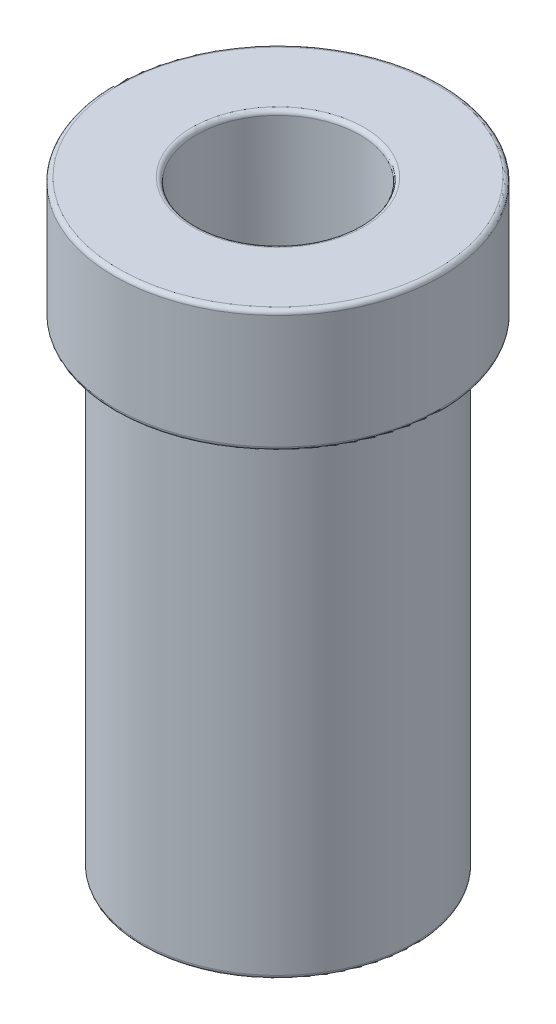
SolidWorks part; units mm, degrees
material "6061 Alloy"
ref_plane "Front Plane" through (0, 0, 0) normal (0, 0, 1) x (1, 0, 0)
ref_plane "Top Plane" through (0, 0, 0) normal (0, 1, 0) x (1, 0, 0)
ref_plane "Right Plane" through (0, 0, 0) normal (1, 0, 0) x (0, 0, -1)
sketch "Sketch1" plane through (0, 0, 0) normal (0, 0, 1) x (1, 0, 0)
  line L0 (0, 0) -> (0, -0.6875) construction
  line L1 (0, -0.6875) -> (0.1563, -0.6875)
  line L2 (0.1563, -0.6875) -> (0.1563, -0.1406)
  line L3 (0.1563, -0.1406) -> (0.1875, -0.1406)
  line L4 (0.1875, -0.1406) -> (0.1875, 0)
  line L5 (0.1875, 0) -> (0, 0)
  line L6 (0, 0) -> (0, -0.6875)
  dimension "D1" = 0.6875
  dimension "D2" = 0.3125
  dimension "D3" = 0.375
  dimension "D4" = 0.1406
revolve "Revolve1" add sketch "Sketch1" angle 360 about L0
sketch "Sketch2" plane through (0, 0, 0) normal (0, 1, 0) x (1, 0, 0)
  circle A0 centre (0, 0) radius 0.0938
  dimension "D1" = 0.1875
extrude "Cut-Extrude1" cut sketch "Sketch2" against normal through all contours A0
fillet "Fillet1" radius 0.005 5 edges at (0, 0, 0.0938) (0, -0.6875, 0.1563) (0, -0.1406, 0.1563) (0, -0.1406, 0.1875) (0, 0, 0.1875)
